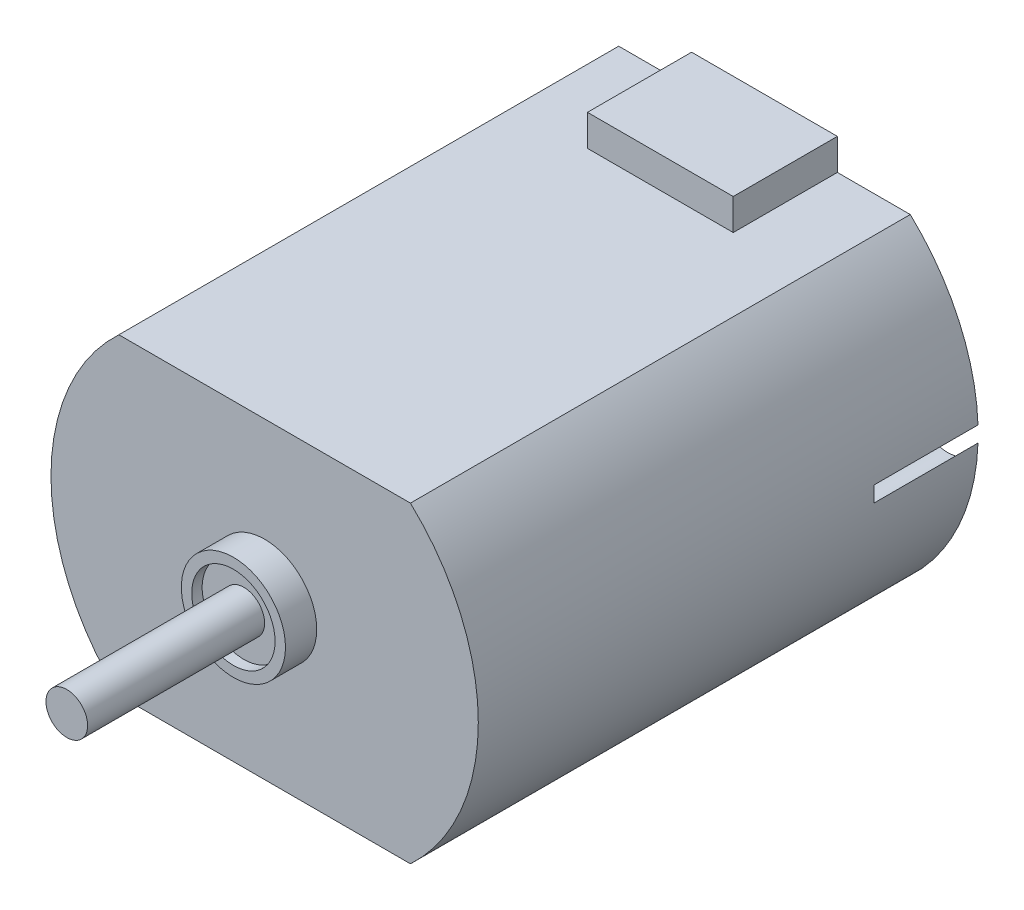
SolidWorks part; units mm, degrees
ref_plane "Alzado" through (0, 0, 0) normal (0, 0, 1) x (1, 0, 0)
ref_plane "Planta" through (0, 0, 0) normal (0, 1, 0) x (1, 0, 0)
ref_plane "Vista lateral" through (0, 0, 0) normal (1, 0, 0) x (0, 0, -1)
sketch "Croquis2" plane through (0, 0, 0) normal (0, 0, 1) x (1, 0, 0)
  line L0 (-7, 7.5) -> (7, 7.5)
  line L1 (-7, -7.5) -> (7, -7.5)
  line L2 (-10.2591, 0) -> (-10.2591, 9.2913) construction
  line L3 (10.2591, 0) -> (9.7409, 10.4917) construction
  arc A0 (-7, 7.5) -> (-7, -7.5) centre (0, 0) ccw
  arc A1 (7, -7.5) -> (7, 7.5) centre (0, 0) ccw
  dimension "D1" = 14
  dimension "D3" = 15
  dimension "D4" = 20
  dimension "D2" = 14
extrude "Saliente-Extruir2" add sketch "Croquis2" along normal blind 19
sketch "Croquis3" plane through (0, 0, 19) normal (0, 0, 1) x (1, 0, 0)
  circle A0 centre (0, 0) radius 2.5
extrude "Saliente-Extruir3" add sketch "Croquis3" along normal blind 1.5
sketch "Croquis4" plane through (0, 0, 20.5) normal (0, 0, 1) x (1, 0, 0)
  circle A0 centre (0, 0) radius 2
  circle A1 centre (0, 0) radius 2.5 construction
  dimension "D1" = 0.5
extrude "Cortar-Extruir1" cut sketch "Croquis4" against normal blind 0.5
sketch "Croquis5" plane through (0, 0, 20) normal (0, 0, 1) x (1, 0, 0)
  circle A0 centre (0, 0) radius 1
extrude "Saliente-Extruir4" add sketch "Croquis5" along normal blind 8.5
sketch "Croquis6" plane through (0, 0, 0) normal (0, 0, -1) x (-1, 0, 0)
  line L0 (-7, 7.5) -> (7, 7.5)
  line L1 (-7, -7.5) -> (7, -7.5)
  line L2 (0, 0) -> (0, 8.3473) construction
  arc A0 (-7, 7.5) -> (-10.2523, 0.3754) centre (0, 0) ccw
  arc A1 (7, -7.5) -> (10.2523, -0.3754) centre (0, 0) ccw
  arc A2 (-10.2523, -0.3754) -> (-10.2523, 0.3754) centre (-8.8, 0) ccw
  arc A3 (10.2523, -0.3754) -> (10.2523, 0.3754) centre (8.8, 0) cw
  arc A4 (-10.2523, -0.3754) -> (-7, -7.5) centre (0, 0) ccw
  arc A5 (10.2523, 0.3754) -> (7, 7.5) centre (0, 0) ccw
  dimension "D1" = 3
extrude "Saliente-Extruir5" add sketch "Croquis6" along normal blind 5
sketch "Croquis7" plane through (0, 0, -5) normal (0, 0, -1) x (-1, 0, 0)
  line L0 (-3, -3.3541) -> (3, -3.3541)
  arc A0 (3, -3.3541) -> (-3, -3.3541) centre (0, 0) ccw
  dimension "D1" = 9
  dimension "D2" = 6
extrude "Saliente-Extruir6" add sketch "Croquis7" along normal blind 2
sketch "Croquis8" plane through (0, 0, -7) normal (0, 0, -1) x (-1, 0, 0)
  circle A0 centre (0, 0) radius 2
extrude "Cortar-Extruir2" cut sketch "Croquis8" against normal blind 0.01
sketch "Croquis9" plane through (0, 0, -6.99) normal (0, 0, -1) x (-1, 0, 0)
  circle A0 centre (0, 0) radius 1
extrude "Saliente-Extruir7" add sketch "Croquis9" along normal blind 0.9
sketch "Croquis10" plane through (0, 0, -5) normal (0, 0, -1) x (-1, 0, 0)
  line L0 (-3.5, 7.5) -> (3.5, 7.5)
  line L1 (7, 7.5) -> (-7, 7.5) construction
  line L2 (-3.5, 7.5) -> (-3.5, 9)
  line L3 (-3.5, 9) -> (3.5, 9)
  line L4 (3.5, 9) -> (3.5, 7.5)
  point P5 (0, 7.5)
  dimension "D1" = 7
  dimension "D2" = 1.5
extrude "Saliente-Extruir8" add sketch "Croquis10" against normal blind 5
